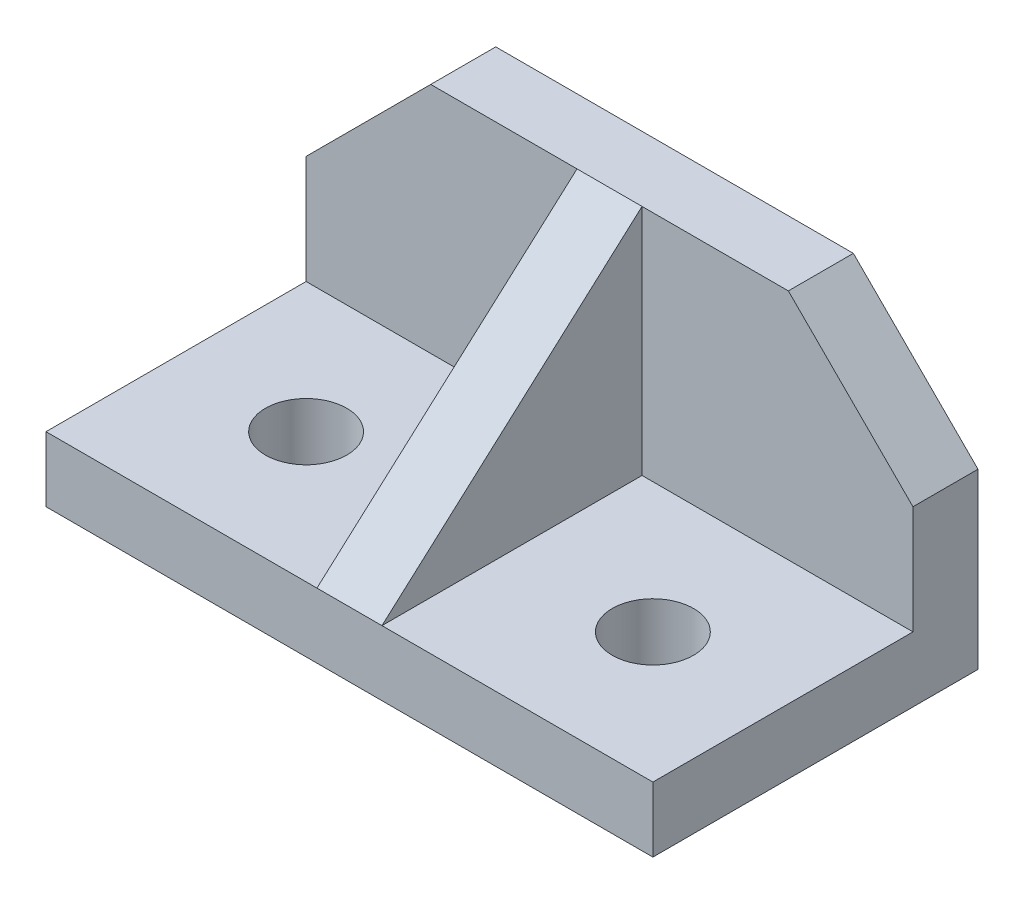
SolidWorks part; units mm, degrees
ref_plane "Front Plane" through (0, 0, 0) normal (0, 0, 1) x (1, 0, 0)
ref_plane "Top Plane" through (0, 0, 0) normal (0, 1, 0) x (1, 0, 0)
ref_plane "Right Plane" through (0, 0, 0) normal (1, 0, 0) x (0, 0, -1)
sketch "Sketch1" plane through (0, 0, 0) normal (0, 1, 0) x (1, 0, 0)
  line L1 (0, 0) -> (112, 0)
  line L2 (0, 0) -> (0, 60)
  line L3 (0, 60) -> (112, 60)
  line L4 (112, 0) -> (112, 60)
  circle A0 centre (24, 24) radius 7.5
  circle A1 centre (88, 24) radius 7.5
  dimension "D5" = 15
  dimension "D1" = 112
  dimension "D2" = 60
  dimension "D3" = 64
  dimension "D4" = 24
  dimension "D6" = 24
  dimension "D7" = 24
extrude "Boss-Extrude1" add sketch "Sketch1" along normal blind 12
sketch "Sketch2" plane through (0, 0, -60) normal (0, 0, -1) x (-1, 0, 0)
  line L0 (0, 12) -> (0, 32)
  line L1 (0, 32) -> (-23, 55)
  line L2 (-23, 55) -> (-89, 55)
  line L3 (-89, 55) -> (-112, 32)
  line L4 (-112, 32) -> (-112, 12)
  line L5 (-112, 12) -> (0, 12)
  dimension "D1" = 32
  dimension "D2" = 55
  dimension "D3" = 45
extrude "Boss-Extrude2" add sketch "Sketch2" against normal blind 12
sketch "Sketch3" plane through (0, 12, 0) normal (0, 1, 0) x (1, 0, 0)
  line L0 (50, 48) -> (50, 0)
  line L1 (112, 48) -> (0, 48) construction
  line L2 (0, 0) -> (112, 0) construction
  line L3 (50, 0) -> (62, 0)
  line L4 (62, 0) -> (62, 48)
  line L5 (62, 48) -> (50, 48)
  circle A0 centre (24, 24) radius 7.5 construction
  dimension "D2" = 26
  dimension "D1" = 12
extrude "Boss-Extrude3" add sketch "Sketch3" along normal blind 43
sketch "Sketch5" plane through (62, 0, 0) normal (1, 0, 0) x (0, 0, -1)
  line L0 (48, 55) -> (0, 12)
  line L1 (0, 12) -> (0, 55)
  line L2 (0, 55) -> (48, 55)
extrude "Cut-Extrude3" cut sketch "Sketch5" against normal blind 123
